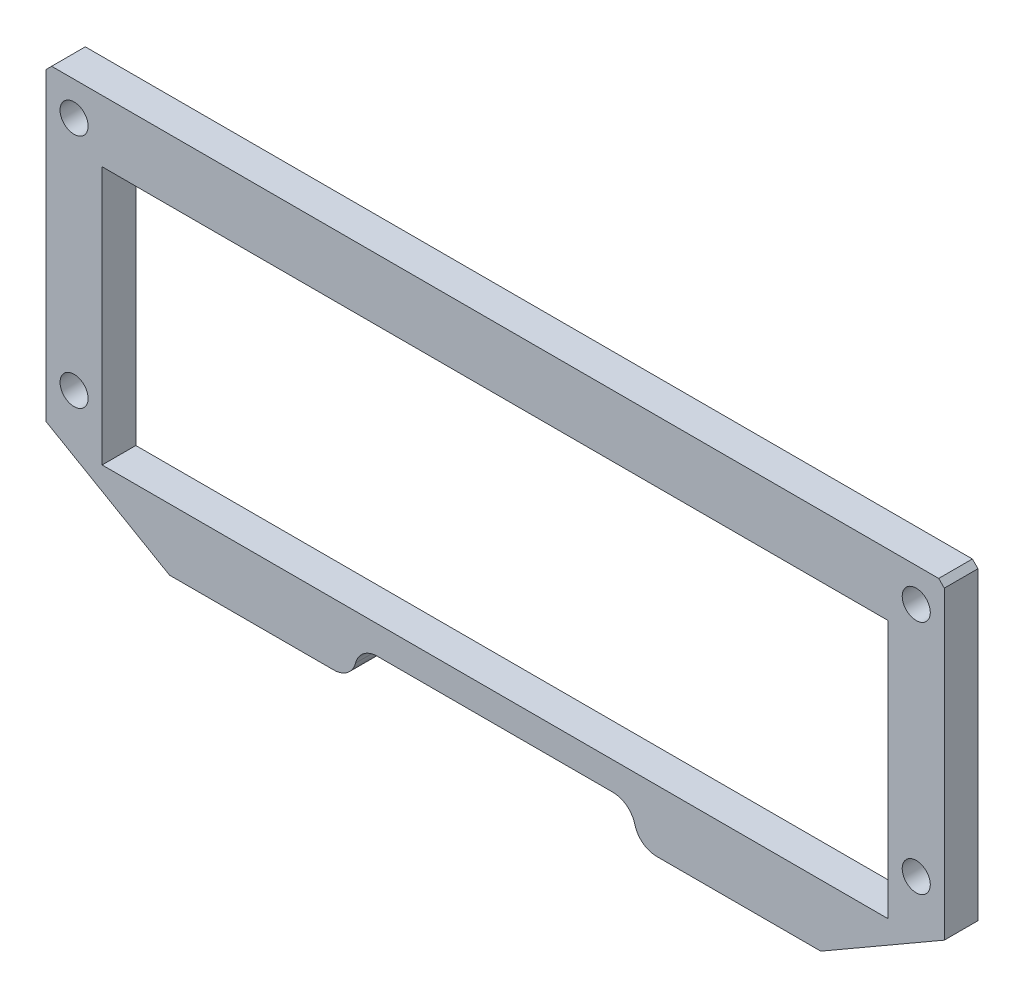
SolidWorks part; units mm, degrees
material "45"
ref_plane "前视基准面" through (0, 0, 0) normal (0, 0, 1) x (1, 0, 0)
ref_plane "上视基准面" through (0, 0, 0) normal (0, 1, 0) x (1, 0, 0)
ref_plane "右视基准面" through (0, 0, 0) normal (1, 0, 0) x (0, 0, -1)
sketch "草图1" plane through (0, 0, 0) normal (0, 0, 1) x (1, 0, 0)
  line L0 (0, 17) -> (0, -17) construction
  line L1 (-40, 17) -> (40, 17)
  line L2 (-40, 17) -> (-40, -17)
  line L3 (-40, -17) -> (40, -17)
  line L4 (40, 17) -> (40, -17)
  dimension "D1" = 80
  dimension "D2" = 34
extrude "拉伸1" add sketch "草图1" along normal blind 3
sketch "草图2" plane through (0, 0, 3) normal (0, 0, 1) x (1, 0, 0)
  line L0 (0, 11.5) -> (0, -11.5) construction
  line L1 (-35, 11.5) -> (35, 11.5)
  line L2 (-35, 11.5) -> (-35, -11.5)
  line L3 (-35, -11.5) -> (35, -11.5)
  line L4 (35, 11.5) -> (35, -11.5)
  dimension "D1" = 23
  dimension "D2" = 70
extrude "拉伸2" cut sketch "草图2" against normal up to surface (3 mm away) up to face at (0, 0, 0)
sketch "草图3" plane through (0, 0, 0) normal (0, 0, 1) x (1, 0, 0)
  line L0 (0, 14) -> (0, -7) construction
  line L1 (-37.5, 14) -> (37.5, 14) construction
  line L2 (-37.5, 14) -> (-37.5, -7) construction
  line L3 (-37.5, -7) -> (37.5, -7) construction
  line L4 (37.5, 14) -> (37.5, -7) construction
  line L5 (40, 17) -> (-40, 17) construction
  circle A0 centre (-37.5, 14) radius 1.5
  circle A1 centre (-37.5, -7) radius 1.5
  circle A2 centre (37.5, 14) radius 1.5
  circle A3 centre (37.5, -7) radius 1.5
  dimension "D3" = 3
  dimension "D1" = 75
  dimension "D2" = 21
  dimension "D4" = 3
extrude "拉伸3" [suppressed] cut sketch "草图3" against normal blind 4
sketch "草图4" [suppressed] plane through (0, -17, 0) normal (0, -1, 0) x (1, 0, 0)
  line L0 (47, 3) -> (27, 3) construction
  line L1 (47, 6) -> (47, 0) construction
  dimension "D1" = 20
hole_wizard "打孔尺寸根据内六角圆柱头螺钉的类型1" [suppressed] positions "3D草图1" profile "草图5" counterbore size "M2.5" standard "GB"
sketch3d "3D草图1" [suppressed]
  point P0 (27, -17, 3)
sketch "草图5" plane through (27, -17, 3) normal (1, 0, 0) x (0, 0, -1)
  line L0 (0, 0) -> (0, 10.8712)
  line L1 (0, 10.8712) -> (1.45, 10)
  line L2 (1.45, 10) -> (1.45, 1.5)
  line L3 (1.45, 1.5) -> (2.5, 1.5)
  line L4 (2.5, 1.5) -> (2.5, 0)
  line L5 (2.5, 0) -> (0, 0)
  line L10 (0, 10.8712) -> (-1.45, 10) construction
  line L11 (0, -6.35) -> (0, 107.95) construction
  dimension "孔直径" = 2.9
  dimension "孔深度" = 10
  dimension "柱形沉头孔直径" = 5
  dimension "柱形沉头孔深度" = 1.5
  dimension "导头角度" = 118
mirror "镜向1" [suppressed] about plane through (0, 0, 0) normal (0, 1, 0)
sketch "草图6" plane through (0, 0, 0) normal (0, 0, 1) x (1, 0, 0)
  line L0 (32, 14) -> (32, -14) construction
  line L1 (0, 0) -> (32, 0) construction
  circle A0 centre (32, 14) radius 1.5
  circle A1 centre (32, -14) radius 1.5
  dimension "D2" = 3
  dimension "D1" = 28
  dimension "D3" = 32
extrude "拉伸4" [suppressed] cut sketch "草图6" against normal blind 10
fillet "圆角1" [suppressed] radius 1
chamfer "倒角1" distance 0.5 angle 45 2 edges at (-40, 17, 1.5) (40, 17, 1.5)
sketch "草图7" plane through (0, 0, 3) normal (0, 0, 1) x (1, 0, 0)
  line L1 (-12.5, -14) -> (12.5, -14)
  line L2 (-12.5, -14) -> (-12.5, -17)
  line L3 (-12.5, -17) -> (12.5, -17)
  line L4 (12.5, -14) -> (12.5, -17)
  line L5 (0, 0) -> (0, -17) construction
  line L6 (-40, -17) -> (40, -17) construction
  dimension "D1" = 3
  dimension "D2" = 25
extrude "拉伸6" cut sketch "草图7" against normal up to surface (3 mm away) up to face at (0, 0, 0)
fillet "圆角2" radius 2 2 edges at (12.5, -14, 1.5) (-12.5, -14, 1.5)
chamfer "倒角2" distance 11 angle 30 1 edges at (40, -17, 1.5)
chamfer "倒角3" distance 11 angle 30 1 edges at (-40, -17, 1.5)
fillet "圆角3" radius 2 2 edges at (12.5, -17, 1.5) (-12.5, -17, 1.5)
hole_wizard "打孔尺寸根据十字槽沉头木螺钉的类型1" [suppressed] positions "3D草图2" profile "草图8" countersink size "M2.5" standard "GB"
sketch3d "3D草图2"
  point P0 (32, 14, 0)
  point P3 (32, -14, 0)
sketch "草图8" plane through (32, 14, 0) normal (1, 0, 0) x (0, 1, 0)
  line L0 (0, 0) -> (0, 3)
  line L1 (0, 3) -> (1.45, 3)
  line L2 (1.45, 3) -> (1.45, 1.25)
  line L3 (1.45, 1.25) -> (2.7, 0)
  line L5 (2.7, 0) -> (0, 0)
  line L6 (-1.45, 1.25) -> (-2.7, 0) construction
  line L11 (0, -6.35) -> (0, 107.95) construction
  dimension "通孔孔直径" = 2.9
  dimension "通孔孔深度" = 3
  dimension "近端锥形沉头孔直径" = 5.4
  dimension "近端锥形沉头孔角度" = 90
hole_wizard "Ø2.5 (2.5) 直径孔1" positions "3D草图3" profile "草图9" hole size "Ø2.5" standard "GB" end condition through all
sketch3d "3D草图3"
  point P0 (-37.5, -7, 0)
  point P3 (-37.5, 14, 0)
  point P6 (37.5, 14, 0)
  point P9 (37.5, -7, 0)
sketch "草图9" plane through (-37.5, -7, 0) normal (1, 0, 0) x (0, 1, 0)
  line L0 (0, 0) -> (0, 3)
  line L1 (0, 3) -> (1.25, 3)
  line L2 (1.25, 3) -> (1.25, 0)
  line L5 (1.25, 0) -> (0, 0)
  line L11 (0, -6.35) -> (0, 107.95) construction
  dimension "Thru Hole Dia." = 2.5
  dimension "Thru Hole Depth" = 3
sketch "Sketch1" plane through (0, 0, 0) normal (0, 0, -1) x (-1, 0, 0)
  line L0 (-40, -10.6491) -> (-40, 16.5) construction
  line L1 (-40, 8) -> (40, 8)
  line L2 (-40, 8) -> (-40, 17)
  line L3 (-40, 17) -> (40, 17)
  line L4 (40, 8) -> (40, 17)
  line L5 (-39.5, 17) -> (39.5, 17) construction
  line L6 (40, 16.5) -> (40, -10.6491) construction
  line L7 (-14.373, -17) -> (-29, -17) construction
  dimension "D1" = 25
extrude "Extrude1" [suppressed] cut sketch "Sketch1" against normal blind 10
sketch "Sketch2" plane through (0, 0, 0) normal (0, 0, -1) x (-1, 0, 0)
  line L0 (-35, -11.5) -> (35, -11.5) construction
  line L1 (-26, -11.5) -> (-23, -11.5)
  line L2 (-26, -11.5) -> (-26, 6.5)
  line L3 (-26, 6.5) -> (-23, 6.5)
  line L4 (-23, -11.5) -> (-23, 6.5)
  line L5 (-40, -10.6491) -> (-40, 16.5) construction
  dimension "D1" = 3
  dimension "D2" = 14
  dimension "D3" = 18
extrude "Extrude2" [suppressed] add sketch "Sketch2" against normal up to surface (3 mm away)
sketch "Sketch3" plane through (0, 0, 3) normal (0, 0, -1) x (-1, 0, 0)
  line L0 (-40, -10.6491) -> (-40, 16.5) construction
  line L1 (-40, 2.5) -> (40, 2.5)
  line L2 (-40, 2.5) -> (-40, -2.5)
  line L3 (-40, -2.5) -> (40, -2.5)
  line L4 (40, 2.5) -> (40, -2.5)
  line L5 (40, 16.5) -> (40, -10.6491) construction
  line L6 (-39.5, 17) -> (39.5, 17) construction
  dimension "D1" = 14.5
  dimension "D2" = 5
extrude "Extrude3" [suppressed] cut sketch "Sketch3" along normal blind 1.2
sketch "草图10" plane through (0, 0, 3) normal (0, 0, 1) x (1, 0, 0)
  line L0 (39.5, 17) -> (-39.5, 17) construction
  line L1 (-35, 11.5) -> (35, 11.5)
  line L2 (-35, 11.5) -> (-35, 17)
  line L3 (-35, 17) -> (35, 17)
  line L4 (35, 11.5) -> (35, 17)
  line L5 (35, -11.5) -> (35, 11.5) construction
extrude "凸台-拉伸1" [suppressed] add sketch "草图10" along normal blind 0.5
